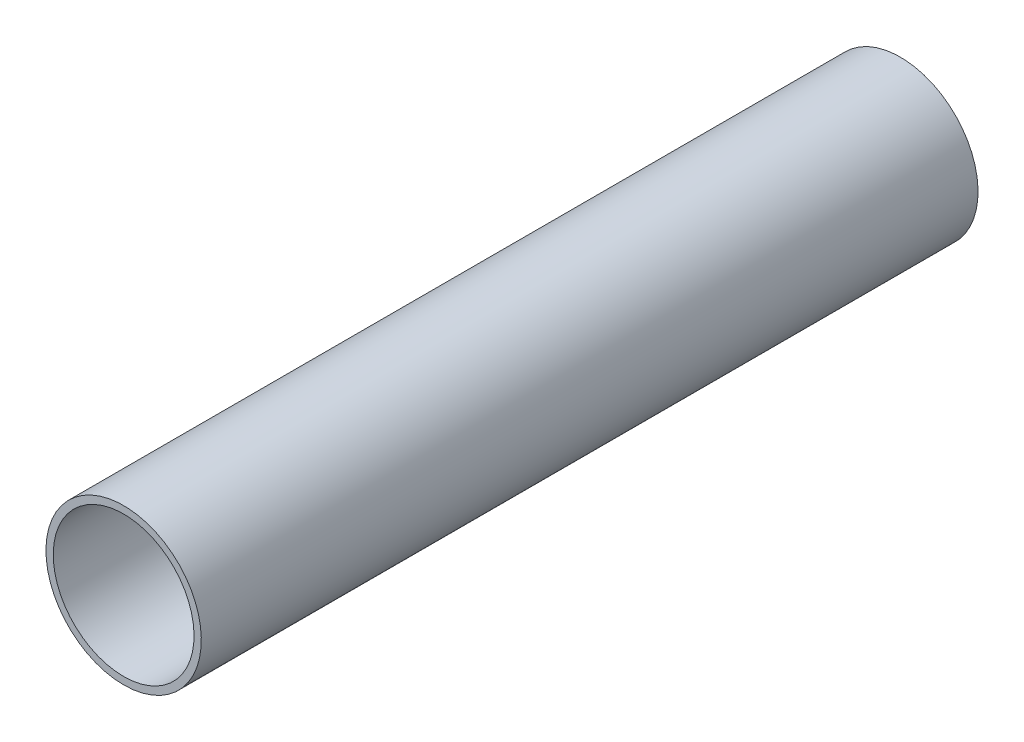
SolidWorks part; units mm, degrees
material "5052 Alloy"
ref_plane "Front Plane" through (0, 0, 0) normal (0, 0, 1) x (1, 0, 0)
ref_plane "Top Plane" through (0, 0, 0) normal (0, 1, 0) x (1, 0, 0)
ref_plane "Right Plane" through (0, 0, 0) normal (1, 0, 0) x (0, 0, -1)
sketch "Sketch1" plane through (0, 0, 0) normal (1, 0, 0) x (0, 0, -1)
  line L0 (-40, 0) -> (40, 0) construction
  line L8 (40, 8) -> (-40, 8)
  line L9 (-40, 8) -> (-40, 7.25)
  line L10 (-40, 7.25) -> (40, 7.25)
  line L11 (40, 7.25) -> (40, 8)
  dimension "D1" = 14.5
  dimension "D2" = 16
  dimension "D3" = 80
revolve "Revolve1" add sketch "Sketch1" angle 360 about L0
